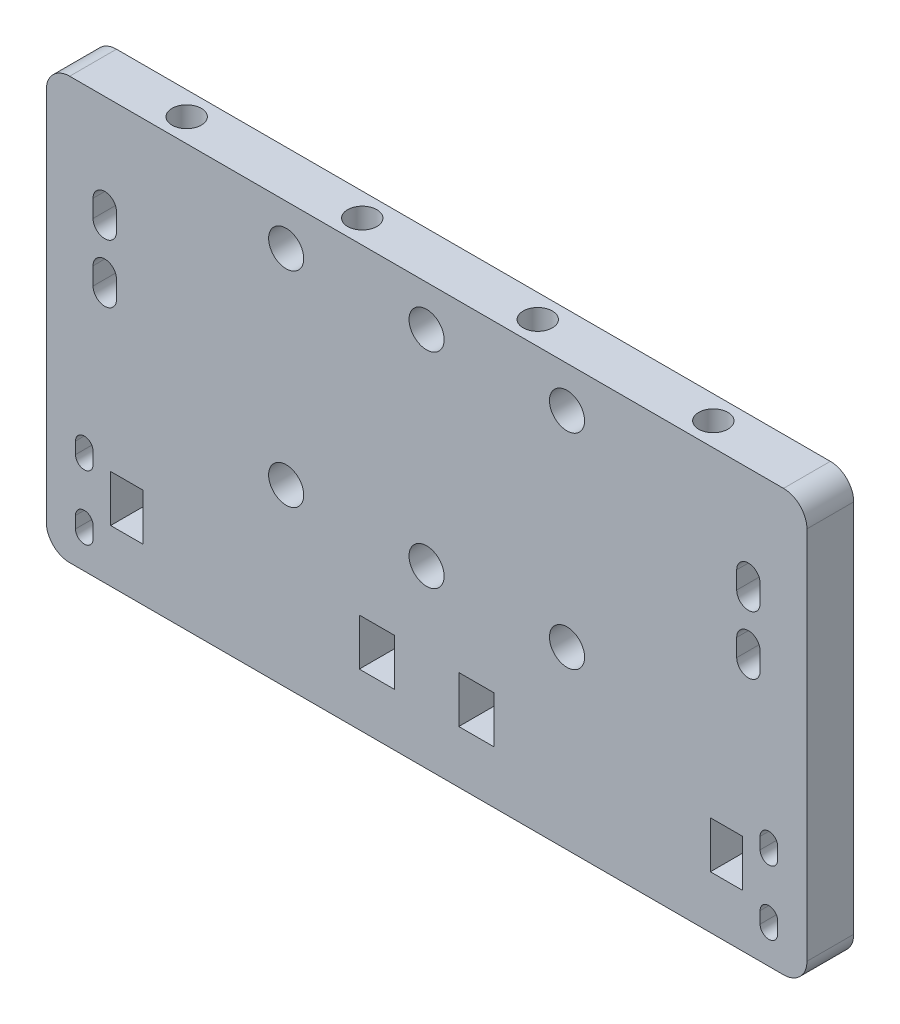
SolidWorks part; units mm, degrees
ref_plane "Plan de face" through (0, 0, 0) normal (0, 0, 1) x (1, 0, 0)
ref_plane "Plan de dessus" through (0, 0, 0) normal (0, 1, 0) x (1, 0, 0)
ref_plane "Plan de droite" through (0, 0, 0) normal (1, 0, 0) x (0, 0, -1)
sketch "Esquisse1" plane through (0, 0, 0) normal (0, 0, 1) x (1, 0, 0)
  line L1 (4, -2.1382) -> (126, -2.1382)
  line L2 (0, 1.8618) -> (0, 17.8618)
  line L3 (4, 69.8618) -> (126, 69.8618)
  line L4 (130, 1.8618) -> (130, 17.8618)
  line L8 (0, 17.8618) -> (0, 65.8618)
  line L9 (65, 69.8618) -> (65, -21.4214) construction
  line L13 (130, 17.8618) -> (130, 65.8618)
  arc A0 (126, 69.8618) -> (130, 65.8618) centre (126, 65.8618) cw
  arc A1 (126, -2.1382) -> (130, 1.8618) centre (126, 1.8618) ccw
  arc A2 (0, 1.8618) -> (4, -2.1382) centre (4, 1.8618) ccw
  arc A3 (0, 65.8618) -> (4, 69.8618) centre (4, 65.8618) cw
  point P6 (130, 69.8618)
  point P9 (130, -2.1382)
  point P12 (0, -2.1382)
  point P26 (0, -2.1382)
  dimension "D3" = 4
  dimension "D1" = 130
  dimension "D2" = 72
extrude "Boss.-Extru.1" add sketch "Esquisse1" along normal blind 8
sketch "Esquisse2" plane through (0, 0, 8) normal (0, 0, 1) x (1, 0, 0)
  line L0 (126, 69.8618) -> (4, 69.8618) construction
  line L1 (11, 6.8618) -> (16.5, 6.8618)
  line L2 (11, 6.8618) -> (11, 14.8618)
  line L3 (11, 14.8618) -> (16.5, 14.8618)
  line L4 (16.5, 6.8618) -> (16.5, 14.8618)
  line L6 (65, 69.8618) -> (65, -2.1382) construction
  line L7 (53.5, 14.8618) -> (59.5, 14.8618)
  line L8 (53.5, 14.8618) -> (53.5, 6.8618)
  line L9 (53.5, 6.8618) -> (59.5, 6.8618)
  line L10 (59.5, 14.8618) -> (59.5, 6.8618)
  line L11 (4, -2.1382) -> (126, -2.1382) construction
  line L12 (76.5, 6.8618) -> (70.5, 6.8618)
  line L13 (70.5, 14.8618) -> (70.5, 6.8618)
  line L14 (76.5, 14.8618) -> (70.5, 14.8618)
  line L15 (76.5, 14.8618) -> (76.5, 6.8618)
  line L16 (119, 6.8618) -> (119, 14.8618)
  line L17 (119, 6.8618) -> (113.5, 6.8618)
  line L18 (113.5, 6.8618) -> (113.5, 14.8618)
  line L19 (119, 14.8618) -> (113.5, 14.8618)
  line L20 (16.5, 6.8618) -> (53.5, 6.8618) construction
  line L21 (76.5, 6.8618) -> (113.5, 6.8618) construction
  line L22 (35, 6.8618) -> (35, -8.2008) construction
  line L23 (95, 6.8618) -> (95, -10.278) construction
  point P12 (56.5, 14.8618)
  dimension "D1" = 55
  dimension "D2" = 8
  dimension "D3" = 5.5
  dimension "D4" = 60
  dimension "D5" = 37
  dimension "D6" = 6
  dimension "D7" = 8
  dimension "D8" = 55
extrude "Enlèv. mat.-Extru.1" cut sketch "Esquisse2" against normal blind 10
sketch "Esquisse9" plane through (0, 69.8618, 0) normal (0, 1, 0) x (1, 0, 0)
  line L0 (0, -4) -> (130, -4) construction
  line L1 (0, -8) -> (0, 0) construction
  line L2 (130, -8) -> (130, 0) construction
  line L3 (65, 0) -> (65, -18.4618) construction
  line L4 (126, 0) -> (4, 0) construction
  circle A0 centre (20, -4) radius 2.5
  circle A1 centre (50, -4) radius 2.5
  circle A2 centre (80, -4) radius 2.5
  circle A3 centre (110, -4) radius 2.5
  dimension "D2" = 5
  dimension "D3" = 20
  dimension "D1" = 4
extrude "Enlèv. mat.-Extru.6" cut sketch "Esquisse9" against normal blind 20
sketch "Esquisse10" plane through (0, 0, 8) normal (0, 0, 1) x (1, 0, 0)
  line L0 (41, 62.8618) -> (41, 27.8618) construction
  line L1 (41, 45.3618) -> (120.8469, 45.3618) construction
  line L3 (65, 69.8618) -> (65, -2.1382) construction
  line L4 (126, 69.8618) -> (4, 69.8618) construction
  line L5 (4, -2.1382) -> (126, -2.1382) construction
  circle A0 centre (41, 62.8618) radius 3
  circle A1 centre (41, 27.8618) radius 3
  circle A2 centre (65, 62.8618) radius 3
  circle A3 centre (65, 27.8618) radius 3
  circle A4 centre (89, 62.8618) radius 3
  circle A5 centre (89, 27.8618) radius 3
  dimension "D1" = 6
  dimension "D5" = 7
  dimension "D2" = 35
  dimension "D4" = 24
  dimension "D3" = 3
extrude "Enlèv. mat.-Extru.7" cut sketch "Esquisse10" against normal through all
sketch "Esquisse18" plane through (0, 0, 0) normal (0, 0, -1) x (-1, 0, 0)
  line L0 (-123.5, 3.3618) -> (-123.5, 5.3618) construction
  line L1 (-125, 3.3618) -> (-125, 5.3618)
  line L2 (-122, 3.3618) -> (-122, 5.3618)
  line L3 (-127.5, 9.8618) -> (-123.5, 9.8618) construction
  line L4 (-127.5, 0.8618) -> (-127.5, 18.8618) construction
  line L5 (-123.5, 16.3618) -> (-123.5, 14.3618) construction
  line L6 (-125, 16.3618) -> (-125, 14.3618)
  line L7 (-122, 16.3618) -> (-122, 14.3618)
  line L8 (-6.5, 3.3618) -> (-6.5, 5.3618) construction
  line L9 (-8, 3.3618) -> (-8, 5.3618)
  line L10 (-5, 3.3618) -> (-5, 5.3618)
  line L11 (-10.5, 9.8618) -> (-8.3796, 9.8618) construction
  line L12 (-10.5, 0.8618) -> (-10.5, 18.8618) construction
  line L13 (-6.5, 16.3618) -> (-6.5, 14.3618) construction
  line L14 (-8, 16.3618) -> (-8, 14.3618)
  line L15 (-5, 16.3618) -> (-5, 14.3618)
  arc A0 (-125, 3.3618) -> (-122, 3.3618) centre (-123.5, 3.3618) ccw
  arc A1 (-122, 5.3618) -> (-125, 5.3618) centre (-123.5, 5.3618) ccw
  arc A2 (-125, 16.3618) -> (-122, 16.3618) centre (-123.5, 16.3618) cw
  arc A3 (-122, 14.3618) -> (-125, 14.3618) centre (-123.5, 14.3618) cw
  arc A4 (-8, 3.3618) -> (-5, 3.3618) centre (-6.5, 3.3618) ccw
  arc A5 (-5, 5.3618) -> (-8, 5.3618) centre (-6.5, 5.3618) ccw
  arc A6 (-8, 16.3618) -> (-5, 16.3618) centre (-6.5, 16.3618) cw
  arc A7 (-5, 14.3618) -> (-8, 14.3618) centre (-6.5, 14.3618) cw
  point P2 (-123.5, 4.3618)
  point P14 (-123.5, 15.3618)
  point P21 (-6.5, 4.3618)
  point P33 (-6.5, 15.3618)
  dimension "D2" = 1.5
  dimension "D4" = 1.5
  dimension "D1" = 2
  dimension "D3" = 2
extrude "Enlèv. mat.-Extru.12" cut sketch "Esquisse18" against normal through all
sketch "Esquisse21" plane through (0, 0, 0) normal (0, 0, -1) x (-1, 0, 0)
  line L0 (-120, 40.8082) -> (-120, 43.8082) construction
  line L1 (-122, 40.8082) -> (-122, 43.8082)
  line L2 (-118, 40.8082) -> (-118, 43.8082)
  line L3 (-120, 42.3082) -> (-120, 52.3082) construction
  line L6 (-120, 47.3082) -> (-127.6769, 47.3082) construction
  line L7 (-120, 53.8082) -> (-120, 50.8082) construction
  line L8 (-122, 53.8082) -> (-122, 50.8082)
  line L9 (-118, 53.8082) -> (-118, 50.8082)
  line L10 (-10, 40.8082) -> (-10, 43.8082) construction
  line L11 (-12, 40.8082) -> (-12, 43.8082)
  line L12 (-8, 40.8082) -> (-8, 43.8082)
  line L13 (-10, 42.3082) -> (-10, 52.3082) construction
  line L14 (-10, 47.3082) -> (-13.577, 47.3082) construction
  line L15 (-10, 53.8082) -> (-10, 50.8082) construction
  line L18 (-12, 53.8082) -> (-12, 50.8082)
  line L19 (-8, 53.8082) -> (-8, 50.8082)
  arc A0 (-122, 40.8082) -> (-118, 40.8082) centre (-120, 40.8082) ccw
  arc A1 (-118, 43.8082) -> (-122, 43.8082) centre (-120, 43.8082) ccw
  circle A4 centre (-120, 42.3082) radius 1.5 construction
  circle A5 centre (-120, 42.3082) radius 1.5 construction
  arc A6 (-122, 53.8082) -> (-118, 53.8082) centre (-120, 53.8082) cw
  arc A7 (-118, 50.8082) -> (-122, 50.8082) centre (-120, 50.8082) cw
  circle A8 centre (-120, 52.3082) radius 1.5 construction
  circle A9 centre (-120, 52.3082) radius 1.5 construction
  circle A10 centre (-120, 52.3082) radius 1.5 construction
  arc A11 (-12, 40.8082) -> (-8, 40.8082) centre (-10, 40.8082) ccw
  arc A12 (-8, 43.8082) -> (-12, 43.8082) centre (-10, 43.8082) ccw
  circle A15 centre (-10, 42.3082) radius 1.5 construction
  circle A16 centre (-10, 42.3082) radius 1.5 construction
  circle A17 centre (-10, 52.3082) radius 1.5 construction
  arc A18 (-12, 53.8082) -> (-8, 53.8082) centre (-10, 53.8082) cw
  arc A19 (-8, 50.8082) -> (-12, 50.8082) centre (-10, 50.8082) cw
  point P2 (-120, 42.3082)
  point P12 (-120, 52.3082)
  point P25 (-10, 42.3082)
  point P40 (-10, 52.3082)
  dimension "D2" = 2
  dimension "D3" = 2
  dimension "D1" = 3
  dimension "D4" = 3
extrude "Enlèv. mat.-Extru.13" cut sketch "Esquisse21" against normal through all
